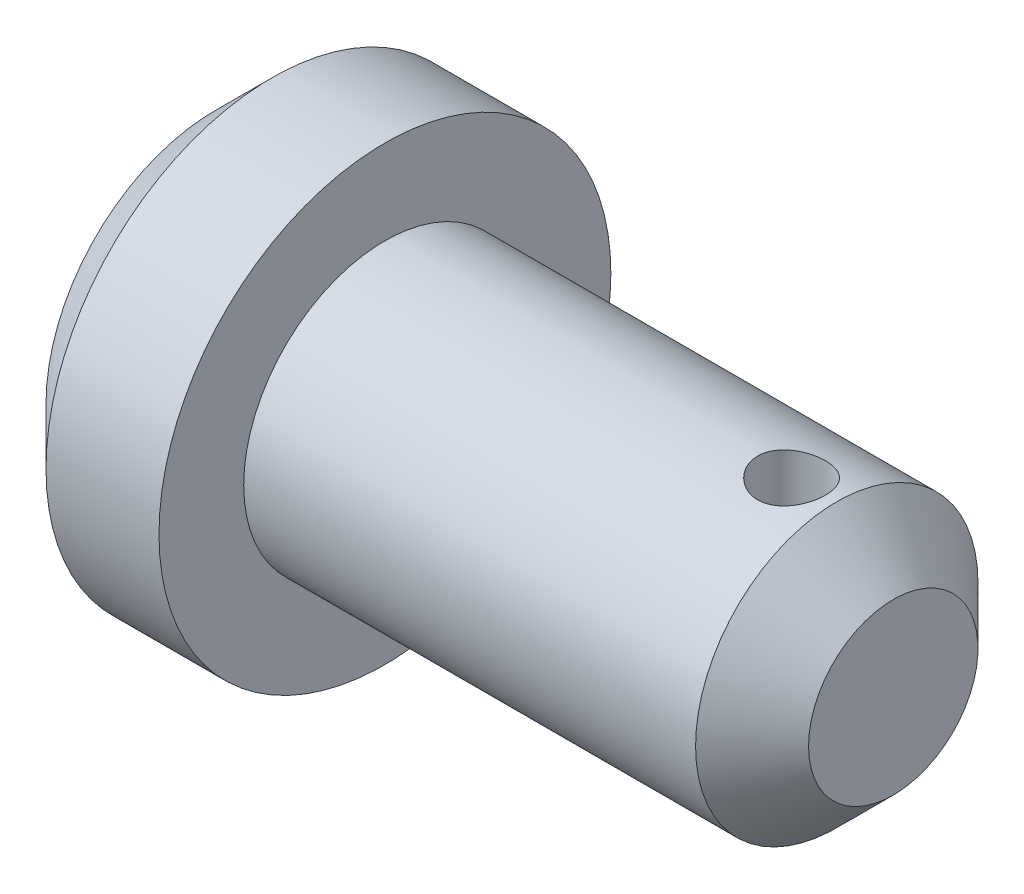
SolidWorks part; units mm, degrees
ref_plane "前基準面" through (0, 0, 0) normal (0, 0, 1) x (1, 0, 0)
ref_plane "上基準面" through (0, 0, 0) normal (0, 1, 0) x (1, 0, 0)
ref_plane "右基準面" through (0, 0, 0) normal (1, 0, 0) x (0, 0, -1)
sketch "草圖1" plane through (0, 0, 0) normal (0, 0, 1) x (1, 0, 0)
  line L1 (0, 0) -> (30, 0)
  line L2 (0, 0) -> (0, 40)
  line L3 (0, 40) -> (30, 40)
  line L4 (30, 0) -> (30, 40)
  line L5 (30, 0) -> (120, 0)
  line L6 (30, 0) -> (30, 25)
  line L7 (30, 25) -> (120, 25)
  line L8 (120, 0) -> (120, 25)
  dimension "D1" = 90
  dimension "D2" = 120
  dimension "D3" = 40
  dimension "D4" = 25
revolve "旋轉1" add sketch "草圖1" angle 360 about L1
chamfer "導角1" distance 10 angle 45 2 edges at (0, 0, 40) (120, 0, 25)
sketch "草圖2" plane through (0, 0, 0) normal (0, 1, 0) x (1, 0, 0)
  line L0 (30, -40) -> (30, 40) construction
  line L2 (102, 0) -> (0, 0)
  circle A0 centre (102, 0) radius 6
  dimension "D1" = 12
  dimension "D2" = 72
extrude "除料-伸長1" cut sketch "草圖2" along normal mid plane 500
